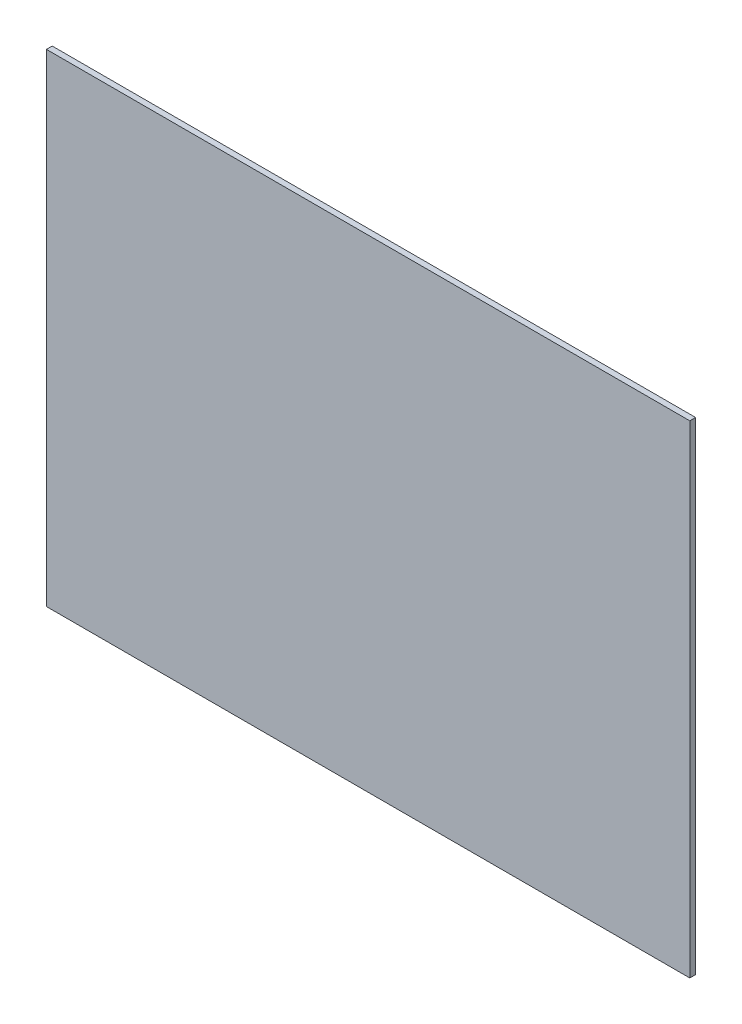
SolidWorks part; units mm, degrees
ref_plane "前视基准面" through (0, 0, 0) normal (0, 0, 1) x (1, 0, 0)
ref_plane "上视基准面" through (0, 0, 0) normal (0, 1, 0) x (1, 0, 0)
ref_plane "右视基准面" through (0, 0, 0) normal (1, 0, 0) x (0, 0, -1)
sketch "草图1" plane through (0, 0, 0) normal (0, 0, 1) x (1, 0, 0)
  line L1 (-200, 150) -> (200, 150)
  line L2 (-200, 150) -> (-200, -150)
  line L3 (-200, -150) -> (200, -150)
  line L4 (200, 150) -> (200, -150)
  line L5 (-200, 150) -> (200, -150) construction
  line L6 (-200, -150) -> (200, 150) construction
  point P0 (0, 0)
  dimension "D1" = 300
  dimension "D2" = 400
extrude "凸台-拉伸1" add sketch "草图1" along normal blind 3.6
